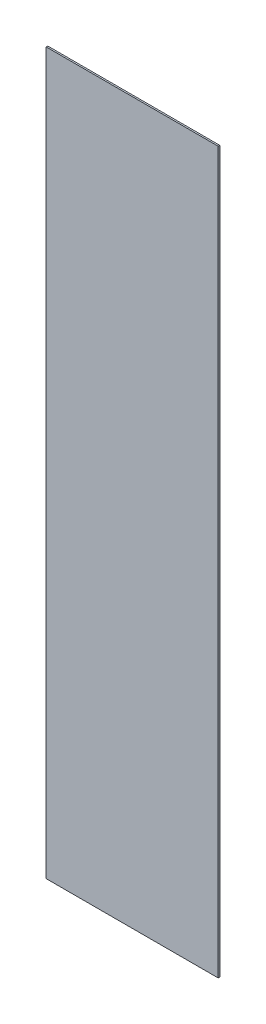
SolidWorks part; units mm, degrees
ref_plane "前基準面" through (0, 0, 0) normal (0, 0, 1) x (1, 0, 0)
ref_plane "上基準面" through (0, 0, 0) normal (0, 1, 0) x (1, 0, 0)
ref_plane "右基準面" through (0, 0, 0) normal (1, 0, 0) x (0, 0, -1)
sketch "草圖1" plane through (0, 0, 0) normal (0, 0, 1) x (1, 0, 0)
  line L1 (-150.4, 629.75) -> (150.4, 629.75)
  line L2 (-150.4, 629.75) -> (-150.4, -629.75)
  line L3 (-150.4, -629.75) -> (150.4, -629.75)
  line L4 (150.4, 629.75) -> (150.4, -629.75)
  line L5 (-150.4, 629.75) -> (150.4, -629.75) construction
  line L6 (-150.4, -629.75) -> (150.4, 629.75) construction
  point P0 (0, 0)
  dimension "D1" = 300.8
  dimension "D2" = 1259.5
extrude "填料-伸長1" add sketch "草圖1" along normal blind 2.75
